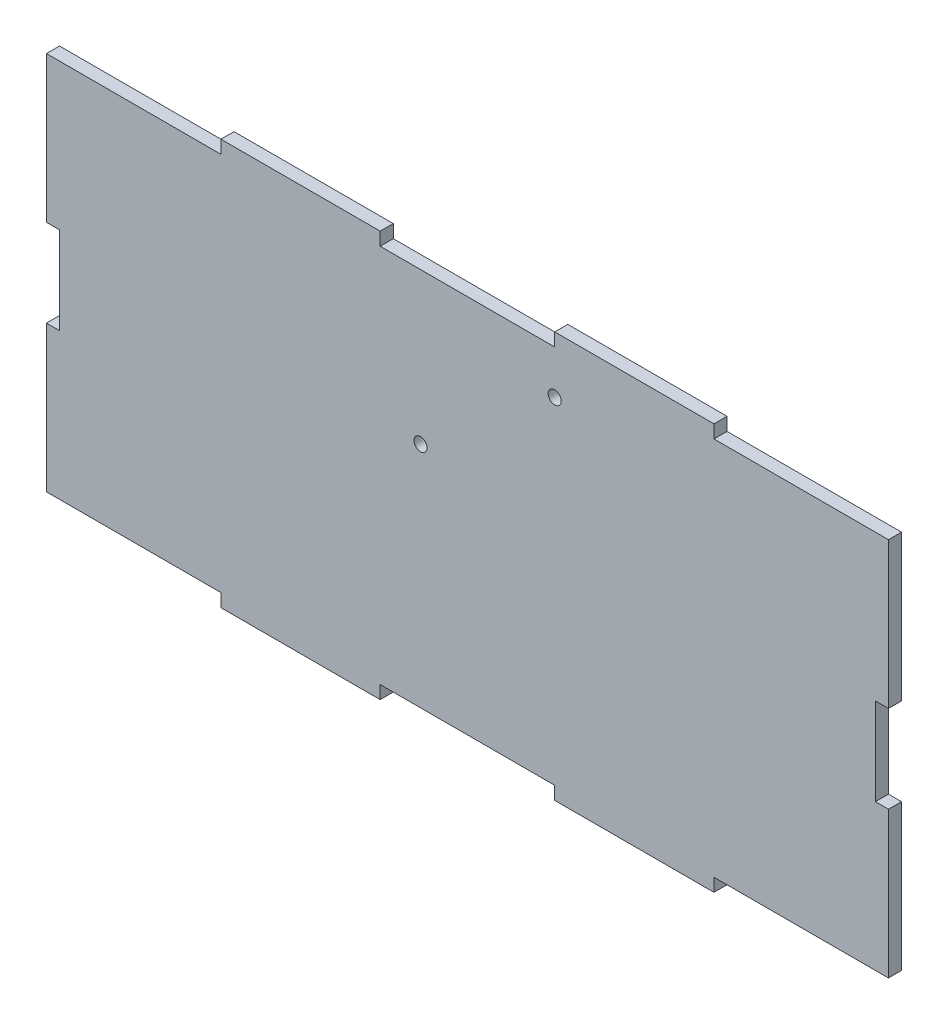
SolidWorks part; units mm, degrees
ref_plane "Front Plane" through (0, 0, 0) normal (0, 0, 1) x (1, 0, 0)
ref_plane "Top Plane" through (0, 0, 0) normal (0, 1, 0) x (1, 0, 0)
ref_plane "Right Plane" through (0, 0, 0) normal (1, 0, 0) x (0, 0, -1)
sketch "Sketch2" plane through (0, 0, 0) normal (0, 0, 1) x (1, 0, 0)
  line L1 (-96.5, 46.5) -> (96.5, 46.5)
  line L2 (-96.5, 46.5) -> (-96.5, -46.5)
  line L3 (-96.5, -46.5) -> (96.5, -46.5)
  line L4 (96.5, 46.5) -> (96.5, -46.5)
  line L5 (-96.5, 46.5) -> (96.5, -46.5) construction
  line L6 (-96.5, -46.5) -> (96.5, 46.5) construction
  point P0 (0, 0)
  dimension "D1" = 193
  dimension "D2" = 93
extrude "Boss-Extrude1" add sketch "Sketch2" along normal blind 3
sketch "Sketch3" plane through (0, 0, 0) normal (0, 0, -1) x (-1, 0, 0)
  line L0 (0, 46.5) -> (0, -46.5) construction
  line L1 (-96.5, 46.5) -> (-56.5, 46.5)
  line L2 (-96.5, 46.5) -> (-96.5, 43.5)
  line L3 (-96.5, 43.5) -> (-56.5, 43.5)
  line L4 (-56.5, 46.5) -> (-56.5, 43.5)
  line L5 (-96.5, 46.5) -> (96.5, 46.5) construction
  line L6 (96.5, -46.5) -> (-96.5, -46.5) construction
  line L7 (-96.5, 0) -> (96.5, 0) construction
  line L8 (-96.5, -46.5) -> (-96.5, 46.5) construction
  line L9 (96.5, 46.5) -> (96.5, -46.5) construction
  line L10 (96.5, -43.5) -> (56.5, -43.5)
  line L11 (96.5, 46.5) -> (56.5, 46.5)
  line L12 (96.5, 46.5) -> (96.5, 43.5)
  line L13 (96.5, 43.5) -> (56.5, 43.5)
  line L14 (56.5, 46.5) -> (56.5, 43.5)
  line L15 (-20, 46.5) -> (20, 46.5)
  line L16 (-20, 46.5) -> (-20, 43.5)
  line L17 (-20, 43.5) -> (20, 43.5)
  line L18 (20, 46.5) -> (20, 43.5)
  line L19 (-20, 46.5) -> (20, 43.5) construction
  line L20 (-20, 43.5) -> (20, 46.5) construction
  line L21 (56.5, -46.5) -> (56.5, -43.5)
  line L22 (96.5, -46.5) -> (56.5, -46.5)
  line L23 (96.5, -46.5) -> (96.5, -43.5)
  line L24 (-20, -43.5) -> (20, -43.5)
  line L25 (20, -46.5) -> (20, -43.5)
  line L26 (-20, -46.5) -> (20, -46.5)
  line L27 (-20, -46.5) -> (-20, -43.5)
  line L28 (-96.5, -43.5) -> (-56.5, -43.5)
  line L29 (-56.5, -46.5) -> (-56.5, -43.5)
  line L30 (-96.5, -46.5) -> (-56.5, -46.5)
  line L31 (-96.5, -46.5) -> (-96.5, -43.5)
  line L32 (96.5, -10) -> (93.5, -10)
  line L33 (-96.5, 10) -> (-93.5, 10)
  line L34 (-96.5, 10) -> (-96.5, -10)
  line L35 (-96.5, -10) -> (-93.5, -10)
  line L36 (-93.5, 10) -> (-93.5, -10)
  line L37 (-96.5, 10) -> (-93.5, -10) construction
  line L38 (-96.5, -10) -> (-93.5, 10) construction
  line L39 (93.5, 10) -> (93.5, -10)
  line L40 (96.5, 10) -> (93.5, 10)
  line L41 (96.5, 10) -> (96.5, -10)
  circle A0 centre (-20, 33.5) radius 1.5
  circle A2 centre (10.759, 8.837) radius 1.5
  point P21 (0, 45)
  point P39 (-95, 0)
  dimension "D11" = 3
  dimension "D13" = 3
  dimension "D1" = 40
  dimension "D2" = 3
  dimension "D3" = 40
  dimension "D4" = 3
  dimension "D5" = 40
  dimension "D6" = 3
  dimension "D7" = 1.5
  dimension "D8" = 3
  dimension "D9" = 20
  dimension "D10" = 1.5
  dimension "D12" = 10
  dimension "D14" = 39.4256
extrude "Cut-Extrude1" cut sketch "Sketch3" against normal blind 3
